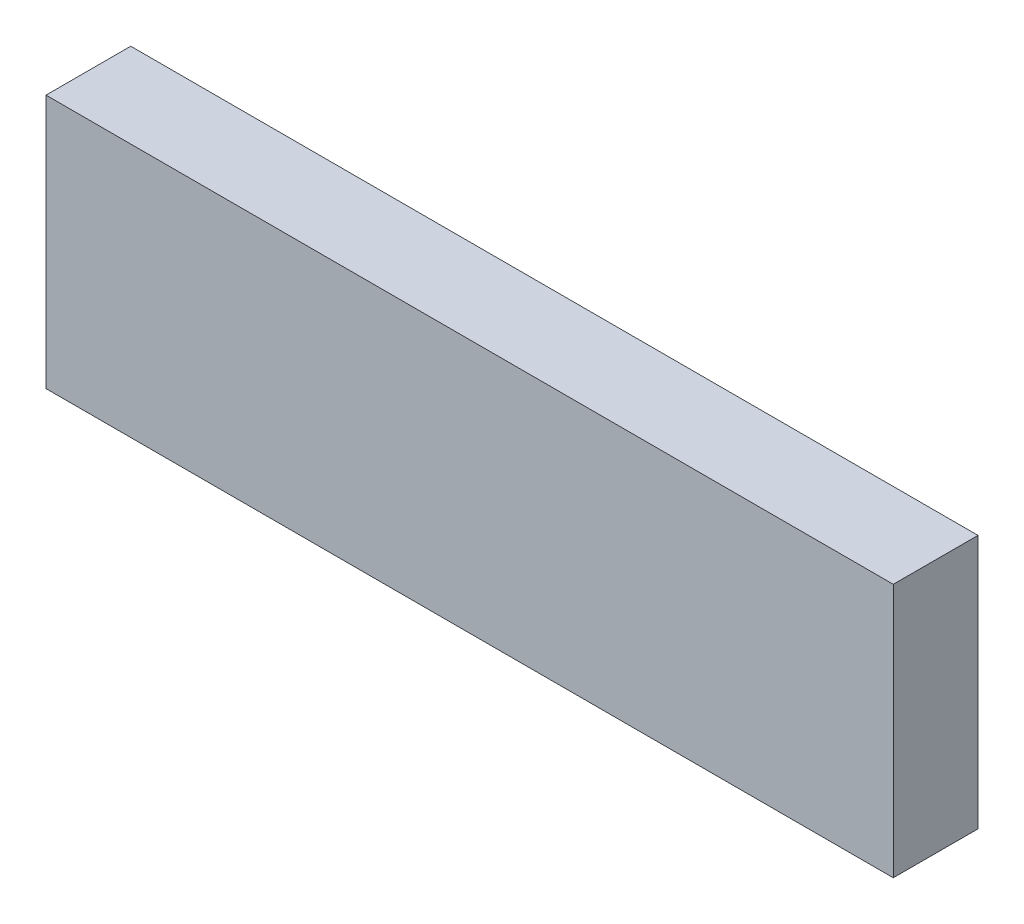
SolidWorks part; units mm, degrees
ref_plane "Front Plane" through (0, 0, 0) normal (0, 0, 1) x (1, 0, 0)
ref_plane "Top Plane" through (0, 0, 0) normal (0, 1, 0) x (1, 0, 0)
ref_plane "Right Plane" through (0, 0, 0) normal (1, 0, 0) x (0, 0, -1)
sketch "Sketch1" plane through (0, 0, 0) normal (0, 0, 1) x (1, 0, 0)
  line L1 (0, 0) -> (-127, 0)
  line L2 (0, 0) -> (0, 38.1)
  line L3 (0, 38.1) -> (-127, 38.1)
  line L4 (-127, 0) -> (-127, 38.1)
  dimension "D1" = 127
  dimension "D2" = 38.1
extrude "Boss-Extrude1" add sketch "Sketch1" along normal blind 12.7
